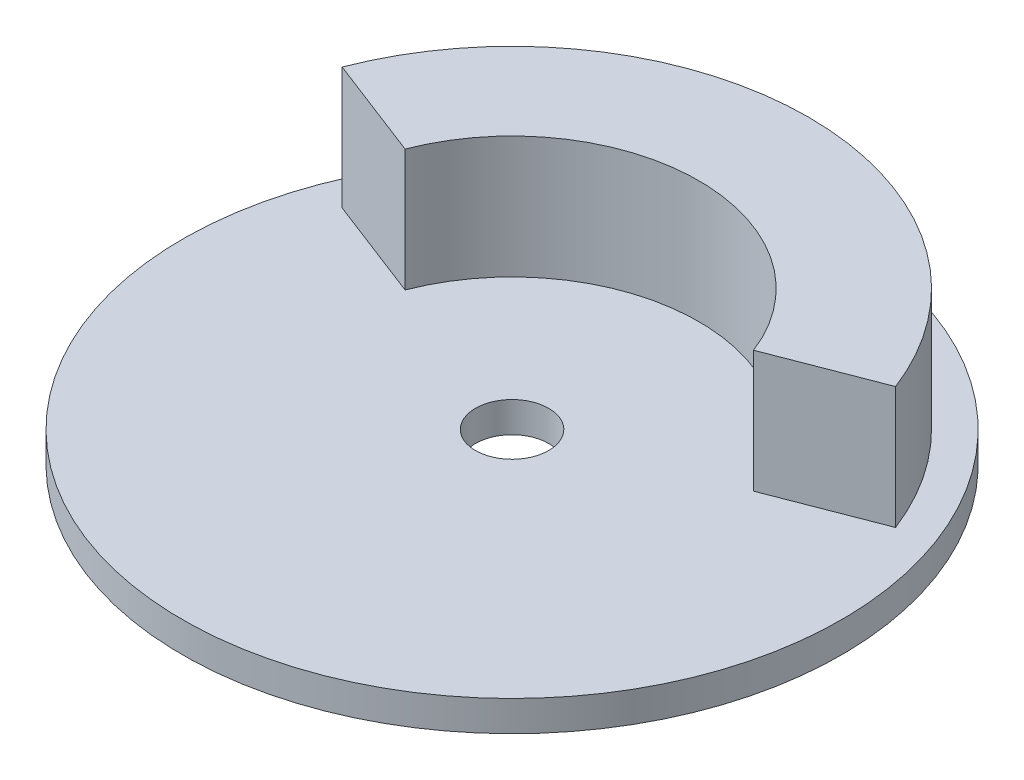
SolidWorks part; units mm, degrees
ref_plane "Front Plane" through (0, 0, 0) normal (0, 0, 1) x (1, 0, 0)
ref_plane "Top Plane" through (0, 0, 0) normal (0, 1, 0) x (1, 0, 0)
ref_plane "Right Plane" through (0, 0, 0) normal (1, 0, 0) x (0, 0, -1)
sketch "Sketch1" plane through (0, 0, 0) normal (0, 1, 0) x (1, 0, 0)
  line L0 (-55, 0) -> (55, 0) construction
  line L1 (-22.6698, 8.7505) -> (-16.656, 24.3305) construction
  line L2 (-22.6698, 8.7505) -> (-14.2736, 5.5095)
  line L3 (0, -55) -> (0, 55) construction
  line L4 (22.6698, 8.7505) -> (14.2736, 5.5095)
  line L5 (-23.78, 5) -> (23.78, 5) construction
  circle A0 centre (0, 0) radius 15.3 construction
  circle A1 centre (0, 0) radius 24.3 construction
  arc A2 (-22.6698, 8.7505) -> (22.6698, 8.7505) centre (0, 0) cw
  arc A3 (-14.2736, 5.5095) -> (14.2736, 5.5095) centre (0, 0) cw
  point P20 (-18.4717, 7.13)
  dimension "D1" = 30.6
  dimension "D2" = 48.6
  dimension "D3" = 2.13
  dimension "D4" = 5
extrude "Boss-Extrude1" add sketch "Sketch1" along normal blind 10 contours A2 L4 A3 L2
sketch "Sketch2" plane through (0, 0, 0) normal (0, -1, 0) x (1, 0, 0)
  circle A1 centre (0, 0) radius 27
  circle A2 centre (0, 0) radius 3
  dimension "D1" = 54
  dimension "D2" = 6
extrude "Boss-Extrude2" add sketch "Sketch2" along normal blind 2.5
